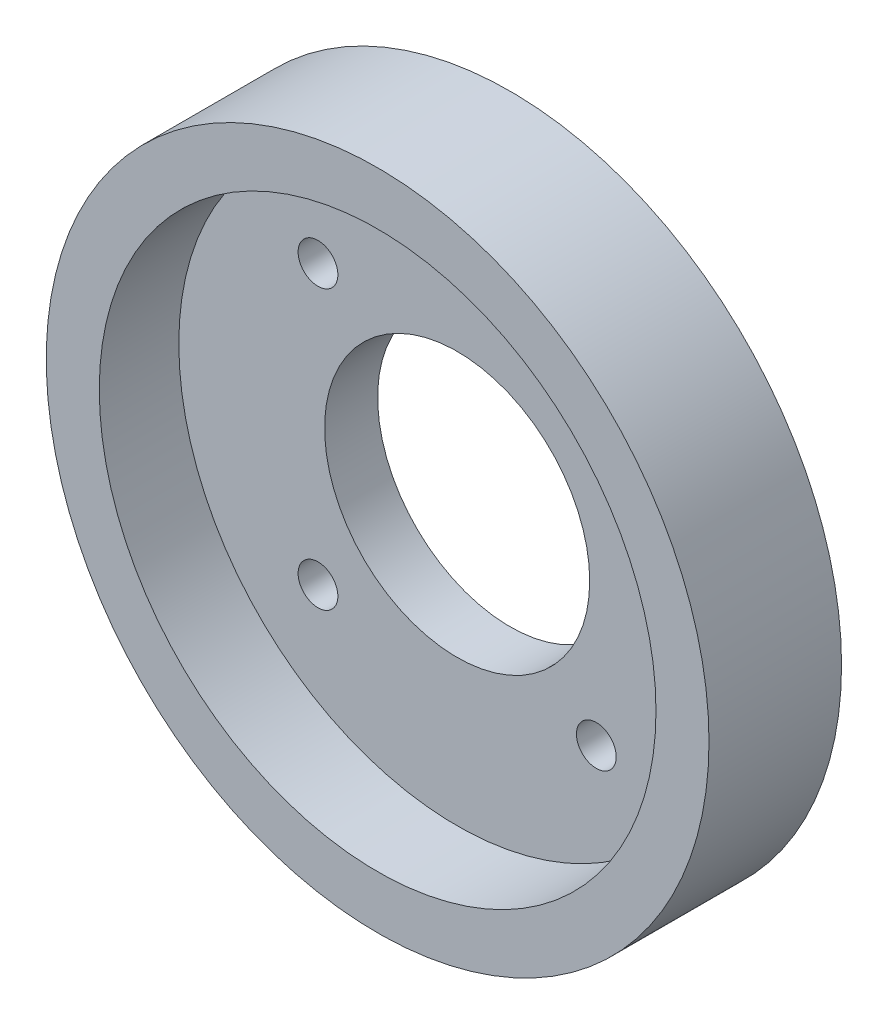
SolidWorks part; units mm, degrees
ref_plane "Plan de face" through (0, 0, 0) normal (0, 0, 1) x (1, 0, 0)
ref_plane "Plan de dessus" through (0, 0, 0) normal (0, 1, 0) x (1, 0, 0)
ref_plane "Plan de droite" through (0, 0, 0) normal (1, 0, 0) x (0, 0, -1)
sketch "Esquisse1" plane through (0, 0, 0) normal (0, 0, 1) x (1, 0, 0)
  line L0 (-10.5, 0) -> (10.5, 0) construction
  line L2 (0, 10.5) -> (0, -10.5) construction
  line L3 (0, -10.5) -> (-10.5, 0) construction
  line L4 (-10.5, 0) -> (0, 10.5) construction
  line L5 (0, 10.5) -> (10.5, 0) construction
  line L6 (10.5, 0) -> (0, -10.5) construction
  circle A0 centre (0, 0) radius 10.5
  circle A1 centre (0, 0) radius 5
  circle A2 centre (0, 0) radius 12.5
  circle A3 centre (-5.25, 5.25) radius 0.75
  circle A4 centre (5.25, 5.25) radius 0.75
  circle A5 centre (5.25, -5.25) radius 0.75
  circle A6 centre (-5.25, -5.25) radius 0.75
  dimension "D1" = 21
  dimension "D2" = 10
  dimension "D3" = 25
  dimension "D4" = 1.5
  dimension "D5" = 1.5
  dimension "D6" = 1.5
  dimension "D7" = 1.5
extrude "Boss.-Extru.1" add sketch "Esquisse1" along normal blind 2 contours A0 A1 | A2 A0
sketch "Esquisse2" plane through (0, 0, 2) normal (0, 0, 1) x (1, 0, 0)
  circle A0 centre (0, 0) radius 12.5
  circle A1 centre (0, 0) radius 10.5
  circle A2 centre (0, 0) radius 12.5 construction
  dimension "D1" = 21
extrude "Boss.-Extru.2" add sketch "Esquisse2" along normal blind 3
